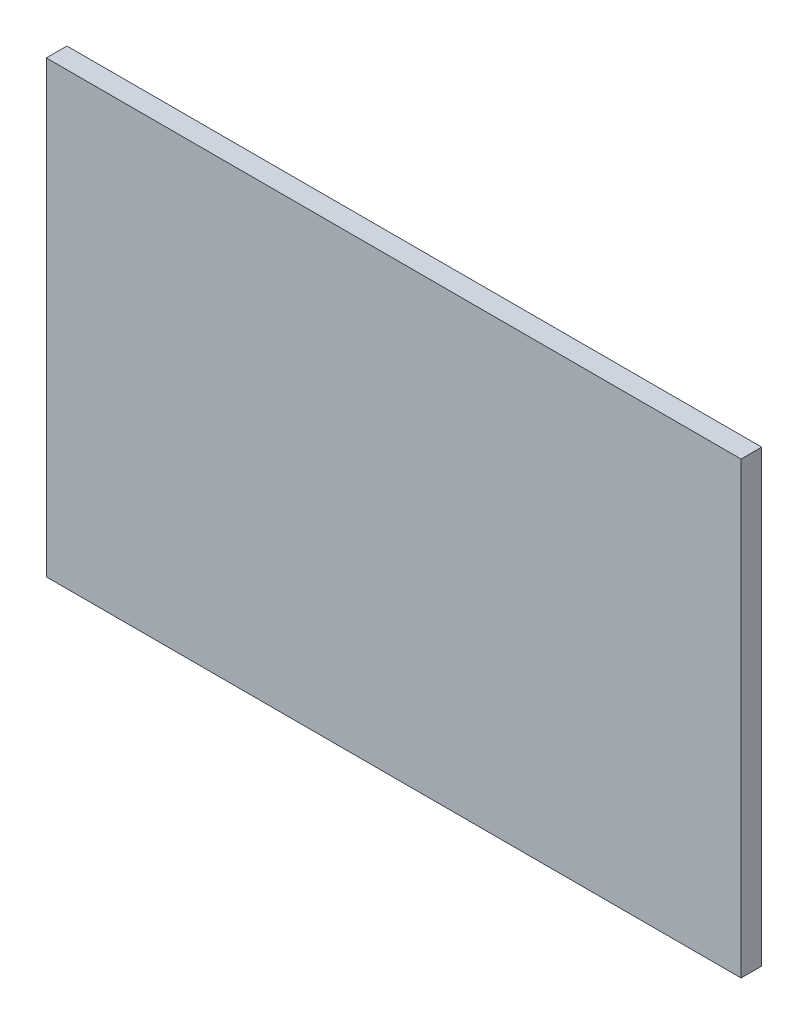
SolidWorks part; units mm, degrees
ref_plane "Front Plane" through (0, 0, 0) normal (0, 0, 1) x (1, 0, 0)
ref_plane "Top Plane" through (0, 0, 0) normal (0, 1, 0) x (1, 0, 0)
ref_plane "Right Plane" through (0, 0, 0) normal (1, 0, 0) x (0, 0, -1)
sketch "Sketch1" plane through (0, 0, 0) normal (0, 0, 1) x (-1, 0, 0)
  line L0 (-84.25, 38.7195) -> (-84.25, -70.2805)
  line L1 (-85, 39.4695) -> (85, 39.4695)
  line L2 (-85, 39.4695) -> (-85, -71.0305)
  line L3 (-85, -71.0305) -> (85, -71.0305)
  line L4 (85, 39.4695) -> (85, -71.0305)
  line L5 (-84.25, -70.2805) -> (84.25, -70.2805)
  line L6 (84.25, 38.7195) -> (84.25, -70.2805)
  line L7 (-84.25, 38.7195) -> (84.25, 38.7195)
  dimension "D2" = 170
  dimension "D3" = 109
  dimension "D1" = 0.75
extrude "Boss-Extrude1" add sketch "Sketch1" along normal blind 5 contours L0 L5 L6 L7
